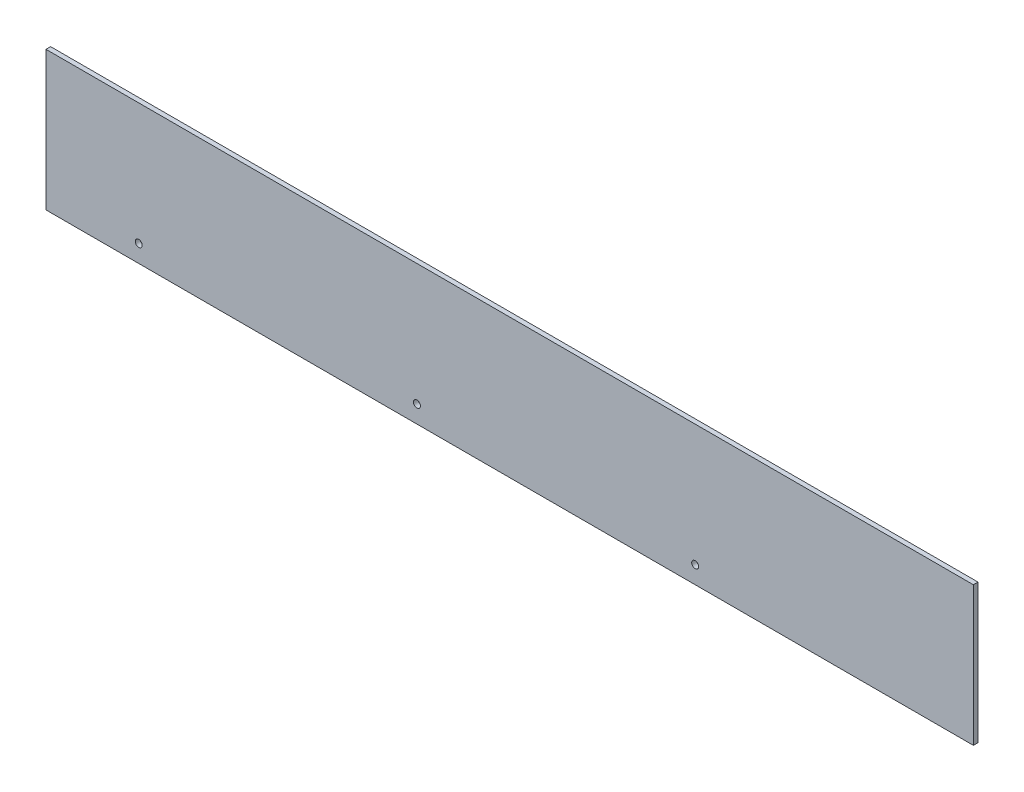
SolidWorks part; units mm, degrees
material "环氧树脂,未充填"
ref_plane "前视基准面" through (0, 0, 0) normal (0, 0, 1) x (1, 0, 0)
ref_plane "上视基准面" through (0, 0, 0) normal (0, 1, 0) x (1, 0, 0)
ref_plane "右视基准面" through (0, 0, 0) normal (1, 0, 0) x (0, 0, -1)
sketch "草图1" plane through (0, 0, 0) normal (0, 0, 1) x (1, 0, 0)
  line L1 (-200, 30) -> (200, 30)
  line L2 (-200, 30) -> (-200, -30)
  line L3 (-200, -30) -> (200, -30)
  line L4 (200, 30) -> (200, -30)
  line L5 (-200, 30) -> (200, -30) construction
  line L6 (-200, -30) -> (200, 30) construction
  point P0 (0, 0)
  dimension "D1" = 60
  dimension "D2" = 400
extrude "凸台-拉伸1" add sketch "草图1" along normal blind 2
sketch "草图2" plane through (0, 0, 2) normal (0, 0, 1) x (1, 0, 0)
  line L0 (-200, -22.5) -> (200, -22.5) construction
  line L1 (-200, 30) -> (-200, -30) construction
  line L2 (200, -30) -> (200, 30) construction
  line L3 (-200, -30) -> (200, -30) construction
  circle A0 centre (-160, -22.5) radius 1.5
  circle A1 centre (-40, -22.5) radius 1.5
  circle A2 centre (80, -22.5) radius 1.5
  dimension "D2" = 40
  dimension "D5" = 3
  dimension "D1" = 7.5
  dimension "D3" = 120
  dimension "D4" = 120
extrude "切除-拉伸1" cut sketch "草图2" against normal through all
